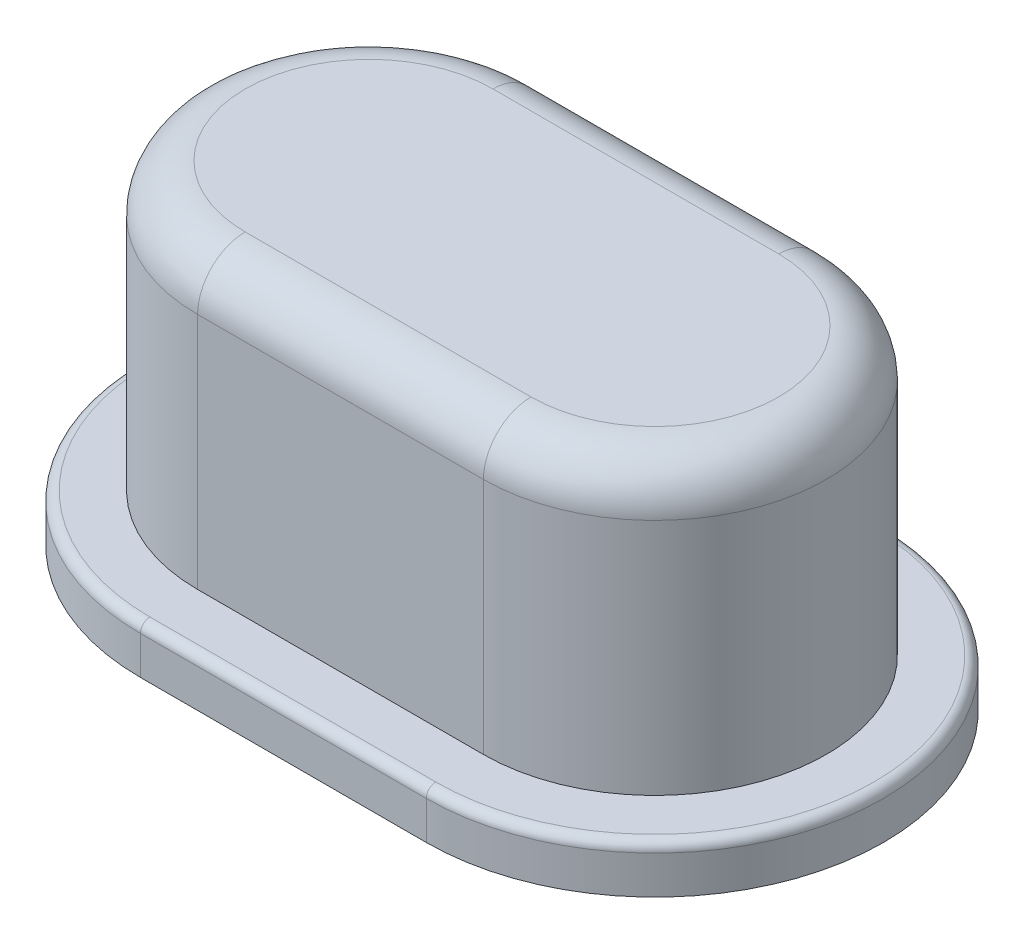
SolidWorks part; units mm, degrees
ref_plane "Front Plane" through (0, 0, 0) normal (0, 0, 1) x (1, 0, 0)
ref_plane "Top Plane" through (0, 0, 0) normal (0, 1, 0) x (1, 0, 0)
ref_plane "Right Plane" through (0, 0, 0) normal (1, 0, 0) x (0, 0, -1)
sketch "Sketch1" plane through (0, 0, 0) normal (0, 1, 0) x (1, 0, 0)
  line L0 (0, 0) -> (0, 3.1646) construction
  line L1 (1.5, 0) -> (-1.5, 0) construction
  line L2 (-1.5, 1.8) -> (1.5, 1.8)
  line L3 (0, 0) -> (0, -3.4617) construction
  line L4 (-1.5, -1.8) -> (1.5, -1.8)
  arc A0 (-1.5, 1.8) -> (-1.5, -1.8) centre (-1.5, 0) ccw
  arc A1 (1.5, 1.8) -> (1.5, -1.8) centre (1.5, 0) cw
  point P9 (0, 1.8)
  point P12 (0, -1.8)
  dimension "D1" = 3.6
  dimension "D2" = 1.5
extrude "Boss-Extrude1" add sketch "Sketch1" along normal blind 3
sketch "Sketch2" plane through (0, 0, 0) normal (0, -1, 0) x (1, 0, 0)
  line L12 (-1.5, -2.4) -> (1.5, -2.4)
  line L13 (1.5, 2.4) -> (-1.5, 2.4)
  line L14 (-1.5, -2.4) -> (1.5, -2.4)
  line L15 (1.5, 2.4) -> (-1.5, 2.4)
  arc A10 (-1.5, 2.4) -> (-1.5, -2.4) centre (-1.5, 0) ccw
  arc A11 (1.5, -2.4) -> (1.5, 2.4) centre (1.5, 0) ccw
  arc A12 (-1.5, 2.4) -> (-1.5, -2.4) centre (-1.5, 0) ccw
  arc A13 (1.5, -2.4) -> (1.5, 2.4) centre (1.5, 0) ccw
  arc M6 (-1.5, 1.8) -> (-1.5, -1.8) centre (-1.5, 0) ccw
  line M7 (-1.5, -1.8) -> (1.5, -1.8)
  arc M8 (1.5, -1.8) -> (1.5, 1.8) centre (1.5, 0) ccw
  line M9 (1.5, 1.8) -> (-1.5, 1.8)
  dimension "D2" = 0.6
extrude "Boss-Extrude2" add sketch "Sketch2" along normal blind 0.5 contours L14 A13 L15 A12 M6 M9 M8 M7 | M9 M6 M7 M8
fillet "Fillet1" radius 0.5 4 edges at (-3.3, 3, 0) (0, 3, -1.8) (3.3, 3, 0) (0, 3, 1.8)
fillet "Fillet2" radius 0.1 4 edges at (3.9, 0, 0) (0, 0, -2.4) (-3.9, 0, 0) (0, 0, 2.4)
